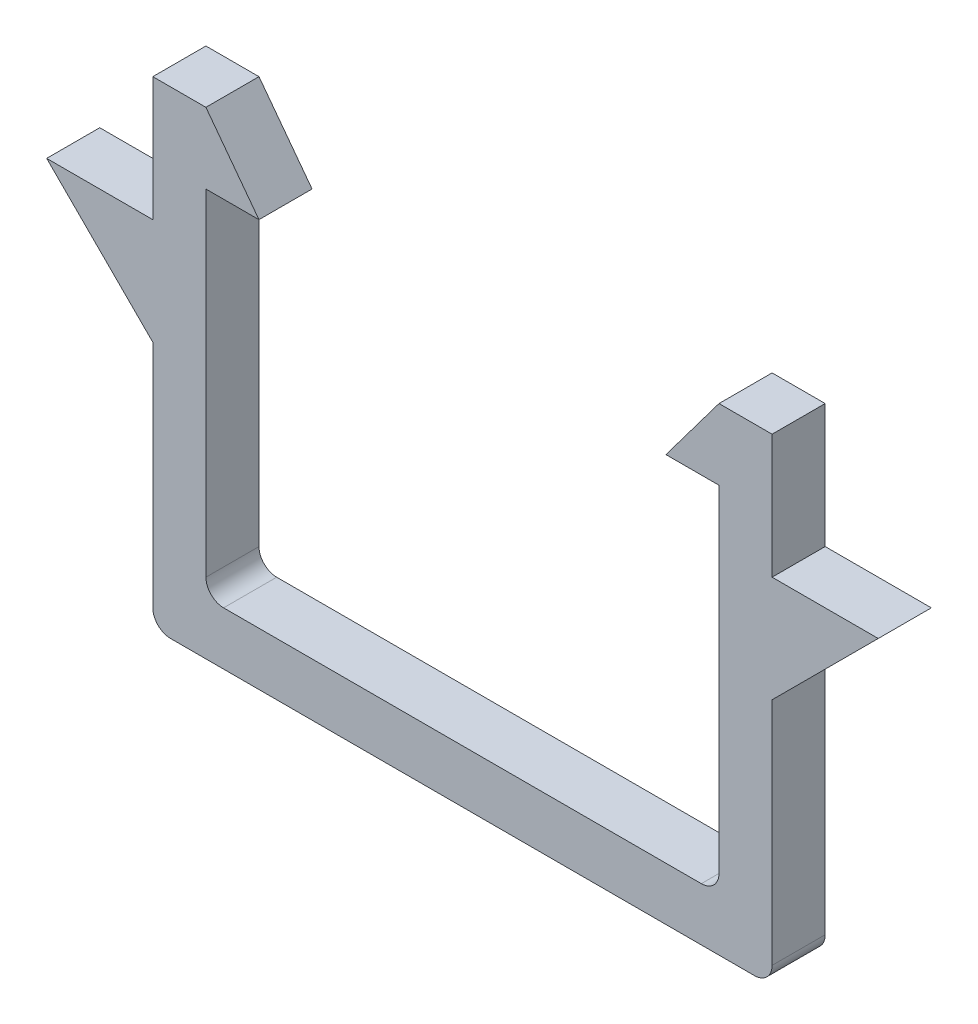
SolidWorks part; units mm, degrees
ref_plane "Front Plane" through (0, 0, 0) normal (0, 0, 1) x (1, 0, 0)
ref_plane "Top Plane" through (0, 0, 0) normal (0, 1, 0) x (1, 0, 0)
ref_plane "Right Plane" through (0, 0, 0) normal (1, 0, 0) x (0, 0, -1)
sketch "Sketch1" plane through (0, 0, 0) normal (0, 0, 1) x (1, 0, 0)
  line L0 (-13.5, 3) -> (13.5, 3)
  line L1 (-14.5, 23) -> (-14.5, 4)
  line L2 (14.5, 4) -> (14.5, 23)
  line L3 (17.5, 1) -> (17.5, 14)
  line L4 (-17.5, 1) -> (-17.5, 14)
  line L5 (-16.5, 0) -> (16.5, 0)
  line L6 (-14.5, 23) -> (-11.5, 23)
  line L9 (14.5, 23) -> (11.5, 23)
  line L12 (17.5, 27) -> (14.5, 27)
  line L13 (-17.5, 27) -> (-14.5, 27)
  line L14 (-14.5, 27) -> (-11.5, 23)
  line L15 (11.5, 23) -> (14.5, 27)
  line L16 (-23.5, 20) -> (-17.5, 14)
  line L17 (-17.5, 20) -> (-23.5, 20)
  line L18 (-17.5, 20) -> (-17.5, 27)
  line L19 (0, -55) -> (0, 55) construction
  line L20 (17.5, 20) -> (23.5, 20)
  line L21 (23.5, 20) -> (17.5, 14)
  line L22 (17.5, 20) -> (17.5, 27)
  arc A0 (17.5, 1) -> (16.5, 0) centre (16.5, 1) cw
  arc A1 (14.5, 4) -> (13.5, 3) centre (13.5, 4) cw
  arc A2 (-16.5, 0) -> (-17.5, 1) centre (-16.5, 1) cw
  arc A3 (-13.5, 3) -> (-14.5, 4) centre (-13.5, 4) cw
  point P5 (-23.5349, 16.1563)
  point P14 (17.5, 0)
  point P17 (14.5, 3)
  point P20 (-17.5, 0)
  point P23 (-14.5, 3)
  point P28 (0, 0)
  point P30 (-20.6208, 19.8799)
  point P31 (0, 0)
  point P32 (-17.5, 14)
  dimension "D12" = 1
  dimension "D2" = 29
  dimension "D3" = 3
  dimension "D4" = 3
  dimension "D5" = 3
  dimension "D6" = 3
  dimension "D7" = 20
  dimension "D8" = 26
  dimension "D9" = 20
  dimension "D10" = 26
  dimension "D11" = 3
  dimension "D13" = 3
  dimension "D14" = 3
  dimension "D15" = 3
  dimension "D16" = 6
  dimension "D17" = 8.4853
extrude "Boss-Extrude1" add sketch "Sketch1" along normal mid plane 3
